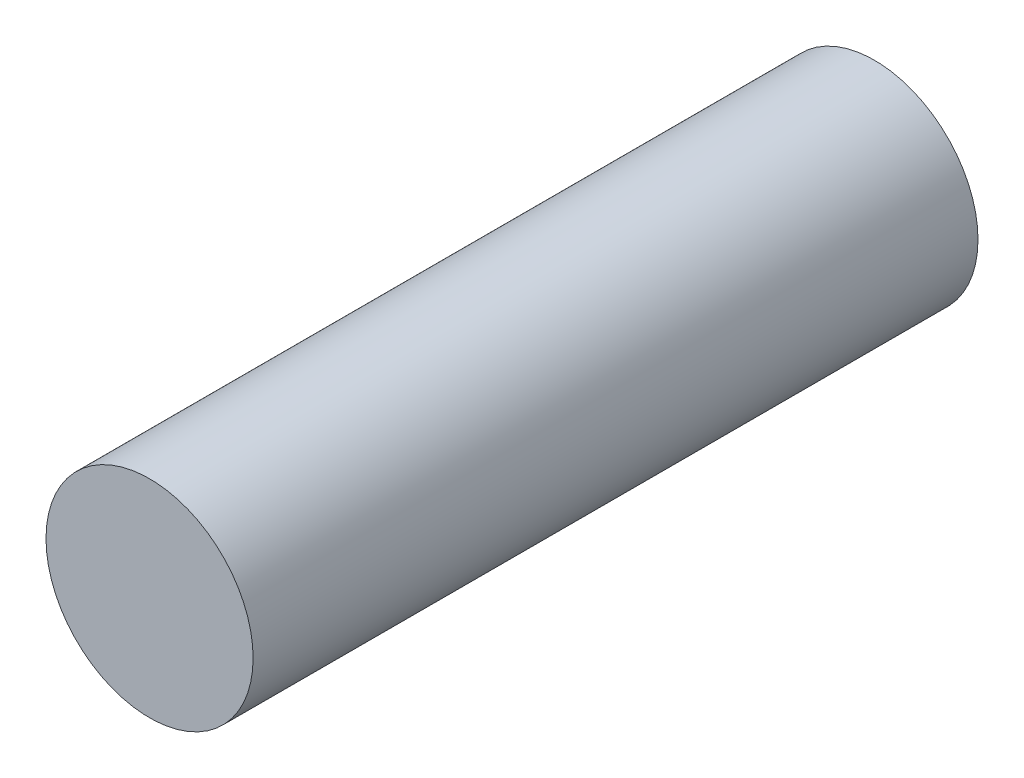
SolidWorks part; units mm, degrees
ref_plane "Front" through (0, 0, 0) normal (0, 0, 1) x (1, 0, 0)
ref_plane "Top" through (0, 0, 0) normal (0, 1, 0) x (1, 0, 0)
ref_plane "Right" through (0, 0, 0) normal (1, 0, 0) x (0, 0, -1)
sketch "Sketch1" plane through (0, 0, 0) normal (0, 0, 1) x (1, 0, 0)
  circle A0 centre (0, 0) radius 5 construction
  circle A1 centre (0, 0) radius 5
extrude "Extrude1" add sketch "Sketch1" against normal up to surface (35 mm away)
